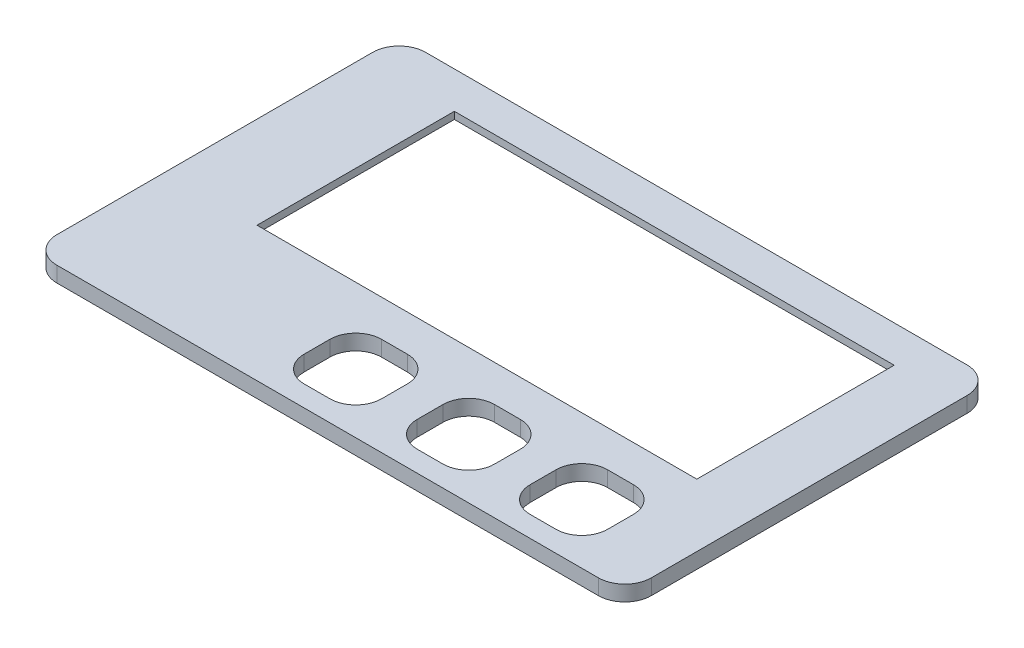
SolidWorks part; units mm, degrees
ref_plane "前视基准面" through (0, 0, 0) normal (0, 0, 1) x (1, 0, 0)
ref_plane "上视基准面" through (0, 0, 0) normal (0, 1, 0) x (1, 0, 0)
ref_plane "右视基准面" through (0, 0, 0) normal (1, 0, 0) x (0, 0, -1)
sketch "草图1" plane through (0, 0, 0) normal (0, 1, 0) x (1, 0, 0)
  line L0 (4.2, -57.3747) -> (88.1748, -57.3747) construction
  line L1 (4.2, 0) -> (88.1748, 0)
  line L2 (0, -4.2) -> (0, -53.1747)
  line L3 (4.2, -57.3747) -> (88.1748, -57.3747)
  line L4 (92.3748, -4.2) -> (92.3748, -53.1747)
  line L5 (88.1748, -57.3747) -> (85.1407, -57.3747) construction
  line L7 (92.3748, -53.1747) -> (92.3748, -50.3851) construction
  line L8 (92.3748, -53.1747) -> (92.3748, -4.2) construction
  line L9 (4.2, -0.1) -> (88.1748, -0.1)
  line L10 (92.2748, -4.2) -> (92.2748, -53.1747)
  line L11 (4.2, -57.2747) -> (88.1748, -57.2747)
  line L12 (0.1, -4.2) -> (0.1, -53.1747)
  line L13 (90.5525, -38.6634) -> (90.5525, -2.6633) construction
  line L14 (35.3194, -42.0531) -> (47.3194, -42.0531)
  line L15 (35.3194, -42.0531) -> (35.3194, -54.0477)
  line L16 (35.3194, -54.0477) -> (47.3194, -54.0477)
  line L17 (47.3194, -42.0531) -> (47.3194, -54.0477)
  line L18 (35.3194, -42.0531) -> (47.3194, -54.0477) construction
  line L19 (35.3194, -54.0477) -> (47.3194, -42.0531) construction
  line L20 (52.8454, -42.0531) -> (64.8454, -42.0531)
  line L21 (52.8454, -42.0531) -> (52.8454, -54.0477)
  line L22 (52.8454, -54.0477) -> (64.8454, -54.0477)
  line L23 (64.8454, -42.0531) -> (64.8454, -54.0477)
  line L24 (52.8454, -42.0531) -> (64.8454, -54.0477) construction
  line L25 (52.8454, -54.0477) -> (64.8454, -42.0531) construction
  line L26 (70.3715, -42.0468) -> (82.3715, -42.0468)
  line L27 (70.3715, -42.0468) -> (70.3715, -54.0477)
  line L28 (70.3715, -54.0477) -> (82.3715, -54.0477)
  line L29 (82.3715, -42.0468) -> (82.3715, -54.0477)
  line L30 (70.3715, -42.0468) -> (82.3715, -54.0477) construction
  line L31 (70.3715, -54.0477) -> (82.3715, -42.0468) construction
  line L32 (82.5525, -5.7904) -> (14.3525, -5.7904)
  line L33 (82.5525, -5.7904) -> (82.5525, -36.3904)
  line L34 (82.5525, -36.3904) -> (14.3525, -36.3904)
  line L35 (14.3525, -5.7904) -> (14.3525, -36.3904)
  line L36 (89.6795, -1.7903) -> (46.5875, -1.7907) construction
  line L39 (79.1416, -1.7904) -> (95.9023, -1.7904) construction
  arc A0 (88.1748, -57.3747) -> (92.3748, -53.1747) centre (88.1748, -53.1747) ccw construction
  arc A1 (92.3748, -4.2) -> (88.1748, 0) centre (88.1748, -4.2) ccw construction
  arc A2 (0, -53.1747) -> (4.2, -57.3747) centre (4.2, -53.1747) ccw construction
  arc A3 (4.2, 0) -> (0, -4.2) centre (4.2, -4.2) ccw construction
  arc A4 (92.3748, -4.2) -> (88.1748, 0) centre (88.1748, -4.2) ccw
  arc A5 (88.1748, -57.3747) -> (92.3748, -53.1747) centre (88.1748, -53.1747) ccw
  arc A6 (0, -53.1747) -> (4.2, -57.3747) centre (4.2, -53.1747) ccw
  arc A7 (4.2, 0) -> (0, -4.2) centre (4.2, -4.2) ccw
  arc A8 (92.2748, -4.2) -> (88.1748, -0.1) centre (88.1748, -4.2) ccw
  arc A9 (88.1748, -57.2747) -> (92.2748, -53.1747) centre (88.1748, -53.1747) ccw
  arc A10 (0.1, -53.1747) -> (4.2, -57.2747) centre (4.2, -53.1747) ccw
  arc A11 (4.2, -0.1) -> (0.1, -4.2) centre (4.2, -4.2) ccw
  point P5 (92.3748, -57.3747)
  point P20 (58.8454, -48.0504)
  point P35 (41.3194, -48.0504)
  point P45 (76.3715, -48.0473)
  dimension "D1" = 0.1
  dimension "D2" = 8
  dimension "D3" = 4
  dimension "D4" = 68.2
  dimension "D5" = 30.6
extrude "凸台-拉伸1" add sketch "草图1" along normal blind 2.4 contours L9 A11 L12 A10 L11 A9 L10 A8
sketch "草图2" plane through (0, 0, 0) normal (0, -1, 0) x (1, 0, 0)
  line L1 (88.1525, 39.5364) -> (4.2063, 39.5364)
  line L2 (90.5525, 37.1364) -> (90.5525, 4.1903)
  line L3 (88.1525, 1.7903) -> (4.2063, 1.7903)
  line L4 (1.8063, 37.1364) -> (1.8063, 4.1903)
  arc A0 (1.8063, 37.1364) -> (4.2063, 39.5364) centre (4.2063, 37.1364) cw
  arc A1 (88.1525, 39.5364) -> (90.5525, 37.1364) centre (88.1525, 37.1364) cw
  arc A2 (88.1525, 1.7903) -> (90.5525, 4.1903) centre (88.1525, 4.1903) ccw
  arc A3 (4.2063, 1.7903) -> (1.8063, 4.1903) centre (4.2063, 4.1903) cw
  dimension "D1" = 2.4
extrude "切除-拉伸1" cut sketch "草图2" against normal offset from surface (1.3 mm away) 1.1 up to face at (48.4525, 2.4, 21.0904)
fillet "圆角1" radius 4 12 edges at (35.3194, 1.2, 54.0477) (52.8454, 1.2, 54.0477) (70.3715, 1.2, 54.0477) (47.3194, 1.2, 54.0477) (64.8454, 1.2, 54.0477) (82.3715, 1.2, 54.0477) (52.8454, 1.2, 42.0531) (70.3715, 1.2, 42.0468) (82.3715, 1.2, 42.0468) (64.8454, 1.2, 42.0531) (47.3194, 1.2, 42.0531) (35.3194, 1.2, 42.0531)
